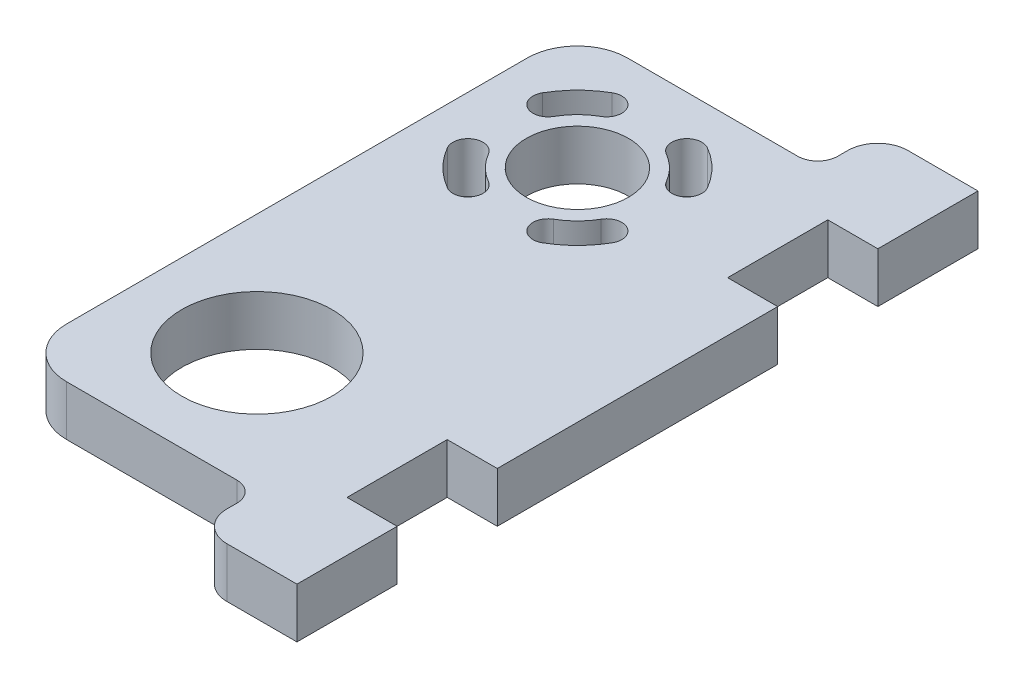
SolidWorks part; units mm, degrees
ref_plane "前视基准面" through (0, 0, 0) normal (0, 0, 1) x (1, 0, 0)
ref_plane "上视基准面" through (0, 0, 0) normal (0, 1, 0) x (1, 0, 0)
ref_plane "右视基准面" through (0, 0, 0) normal (1, 0, 0) x (0, 0, -1)
sketch "草图1" plane through (0, 0, 0) normal (0, 1, 0) x (1, 0, 0)
  line L0 (5, 0) -> (22, 0)
  line L1 (24, -2) -> (24, -3)
  line L2 (27, -6) -> (34, -6)
  line L3 (34, -6) -> (34, 4)
  line L4 (34, 62) -> (27, 62)
  line L5 (24, 59) -> (24, 58)
  line L6 (22, 56) -> (5, 56)
  line L7 (0, 51) -> (0, 5)
  line L8 (12, 57.6955) -> (12, -6.7293) construction
  line L9 (-6.706, 44) -> (33.0543, 44) construction
  line L10 (29, 68.1134) -> (29, -12.8423) construction
  line L11 (34, 52) -> (34, 62)
  line L12 (29, 52) -> (34, 52)
  line L13 (29, 52) -> (29, 42)
  line L14 (29, 42) -> (34, 42)
  line L16 (-6.706, 12) -> (36.7447, 12) construction
  line L17 (29, 14) -> (34, 14)
  line L18 (29, 14) -> (29, 4)
  line L19 (29, 4) -> (34, 4)
  line L21 (34, 14) -> (34, 42)
  circle A0 centre (12, 44) radius 5.1
  circle A1 centre (12, 12) radius 7.5
  circle A2 centre (12, 44) radius 8 construction
  arc A3 (5.0718, 48) -> (8, 50.9282) centre (12, 44) cw construction
  arc A4 (7.25, 52.2272) -> (3.7728, 48.75) centre (12, 44) ccw
  arc A5 (8.75, 49.6292) -> (6.3708, 47.25) centre (12, 44) ccw
  arc A6 (8.75, 49.6292) -> (7.25, 52.2272) centre (8, 50.9282) ccw
  arc A7 (3.7728, 48.75) -> (6.3708, 47.25) centre (5.0718, 48) ccw
  arc A8 (16, 50.9282) -> (18.9282, 48) centre (12, 44) cw construction
  arc A9 (20.2272, 48.75) -> (16.75, 52.2272) centre (12, 44) ccw
  arc A10 (17.6292, 47.25) -> (15.25, 49.6292) centre (12, 44) ccw
  arc A11 (17.6292, 47.25) -> (20.2272, 48.75) centre (18.9282, 48) ccw
  arc A12 (16.75, 52.2272) -> (15.25, 49.6292) centre (16, 50.9282) ccw
  arc A13 (18.9282, 40) -> (16, 37.0718) centre (12, 44) cw construction
  arc A14 (16.75, 35.7728) -> (20.2272, 39.25) centre (12, 44) ccw
  arc A15 (15.25, 38.3708) -> (17.6292, 40.75) centre (12, 44) ccw
  arc A16 (15.25, 38.3708) -> (16.75, 35.7728) centre (16, 37.0718) ccw
  arc A17 (20.2272, 39.25) -> (17.6292, 40.75) centre (18.9282, 40) ccw
  arc A18 (8, 37.0718) -> (5.0718, 40) centre (12, 44) cw construction
  arc A19 (3.7728, 39.25) -> (7.25, 35.7728) centre (12, 44) ccw
  arc A20 (6.3708, 40.75) -> (8.75, 38.3708) centre (12, 44) ccw
  arc A21 (6.3708, 40.75) -> (3.7728, 39.25) centre (5.0718, 40) ccw
  arc A22 (7.25, 35.7728) -> (8.75, 38.3708) centre (8, 37.0718) ccw
  arc A23 (24, -3) -> (27, -6) centre (27, -3) ccw
  arc A24 (27, 62) -> (24, 59) centre (27, 59) ccw
  arc A25 (5, 0) -> (0, 5) centre (5, 5) cw
  arc A26 (5, 56) -> (0, 51) centre (5, 51) ccw
  arc A27 (24, 58) -> (22, 56) centre (22, 58) cw
  arc A28 (22, 0) -> (24, -2) centre (22, -2) cw
  point P14 (12, 44)
  point P19 (17.6569, 49.6569)
  point P24 (24, -6)
  point P35 (17.6569, 38.3431)
  point P38 (6.3431, 49.6569)
  point P51 (6.3431, 38.3431)
  point P56 (16.7088, 44)
  point P59 (0, 0)
  point P62 (12, 44)
  point P65 (24.8114, 46.5679)
  dimension "D11" = 3
  dimension "D12" = 5
  dimension "D13" = 15
  dimension "D14" = 10.2
  dimension "D15" = 16
  dimension "D16" = 4
  dimension "D22" = 2
  dimension "D1" = 32
  dimension "D2" = 56
  dimension "D3" = 12
  dimension "D4" = 12
  dimension "D5" = 12
  dimension "D6" = 24
  dimension "D7" = 24
  dimension "D8" = 6
  dimension "D9" = 6
  dimension "D10" = 10
  dimension "D17" = 5
  dimension "D18" = 10
  dimension "D19" = 10
  dimension "D20" = 10
  dimension "D21" = 10
extrude "凸台-拉伸1" add sketch "草图1" along normal blind 5
